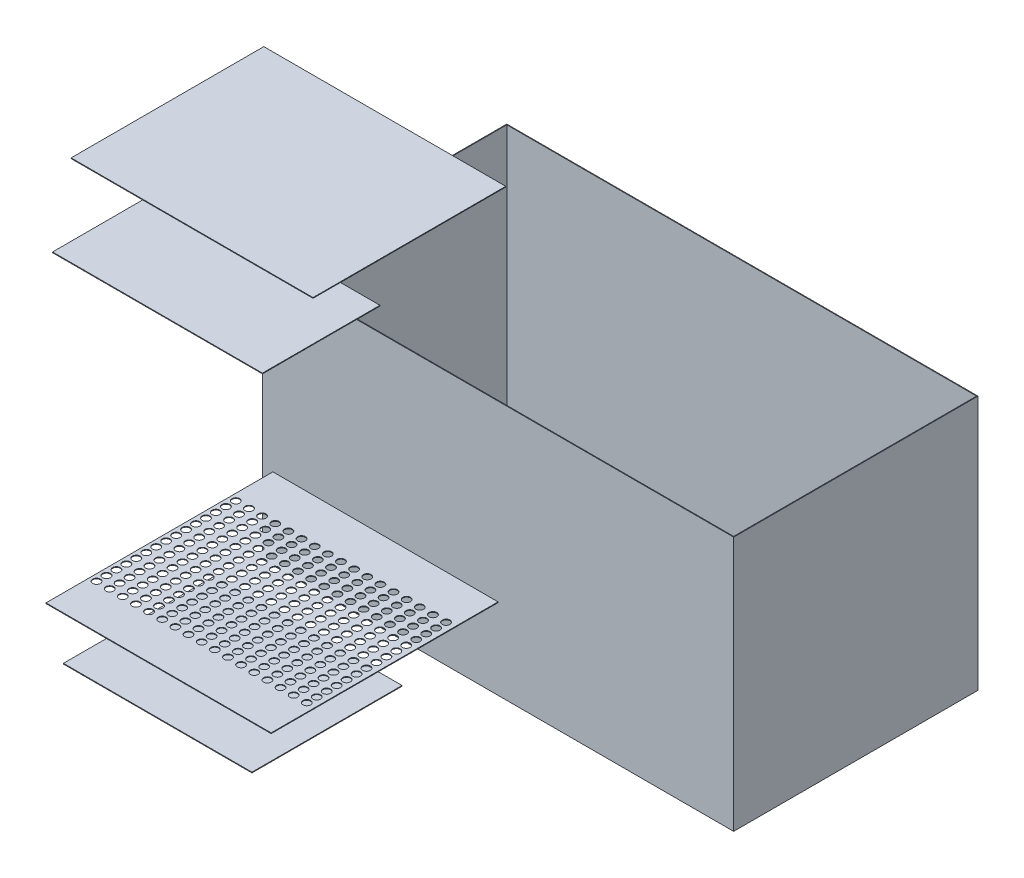
SolidWorks part; units mm, degrees
ref_plane "Спереди" through (0, 0, 0) normal (0, 0, 1) x (1, 0, 0)
ref_plane "Сверху" through (0, 0, 0) normal (0, 1, 0) x (1, 0, 0)
ref_plane "Справа" through (0, 0, 0) normal (1, 0, 0) x (0, 0, -1)
sketch "MASTER_FOOTPRINT" plane through (0, 0, 0) normal (0, 1, 0) x (1, 0, 0)
  line L1 (0, 0) -> (1350, 0)
  line L2 (0, 0) -> (0, 700)
  line L3 (0, 700) -> (1350, 700)
  line L4 (1350, 0) -> (1350, 700)
  dimension "D1" = 1350
  dimension "D2" = 700
extrude "BATH_BASE_PLATE" add sketch "MASTER_FOOTPRINT" along normal blind 750
shell "BATH_SHELL_2MM" thickness 2
sketch "Эскиз1" plane through (0, 0, 0) normal (0, 1, 0) x (1, 0, 0)
  line L1 (80, -220) -> (620, -220)
  line L2 (80, -220) -> (80, -650)
  line L3 (80, -650) -> (620, -650)
  line L4 (620, -220) -> (620, -650)
extrude "INLET_IMPACT_BAFFLE" add sketch "Эскиз1" along normal blind 2 from offset 125 separate body
sketch "Эскиз2" plane through (0, 0, 0) normal (0, 1, 0) x (1, 0, 0)
  line L0 (2, 2) -> (1348, 2) construction
  line L1 (30, 2) -> (675, 2)
  line L2 (30, 2) -> (30, -650)
  line L3 (30, -650) -> (675, -650)
  line L4 (675, 2) -> (675, -650)
  circle A0 centre (48.8235, -125) radius 11
  circle A1 centre (48.8235, -153.5) radius 11
  circle A2 centre (48.8235, -182) radius 11
  circle A3 centre (48.8235, -210.5) radius 11
  circle A4 centre (48.8235, -239) radius 11
  circle A5 centre (48.8235, -267.5) radius 11
  circle A6 centre (48.8235, -296) radius 11
  circle A7 centre (48.8235, -324.5) radius 11
  circle A8 centre (48.8235, -353) radius 11
  circle A9 centre (48.8235, -381.5) radius 11
  circle A10 centre (48.8235, -410) radius 11
  circle A11 centre (48.8235, -438.5) radius 11
  circle A12 centre (48.8235, -467) radius 11
  circle A13 centre (48.8235, -495.5) radius 11
  circle A14 centre (48.8235, -524) radius 11
  circle A15 centre (86.4706, -125) radius 11
  circle A16 centre (86.4706, -153.5) radius 11
  circle A17 centre (86.4706, -182) radius 11
  circle A18 centre (86.4706, -210.5) radius 11
  circle A19 centre (86.4706, -239) radius 11
  circle A20 centre (86.4706, -267.5) radius 11
  circle A21 centre (86.4706, -296) radius 11
  circle A22 centre (86.4706, -324.5) radius 11
  circle A23 centre (86.4706, -353) radius 11
  circle A24 centre (86.4706, -381.5) radius 11
  circle A25 centre (86.4706, -410) radius 11
  circle A26 centre (86.4706, -438.5) radius 11
  circle A27 centre (86.4706, -467) radius 11
  circle A28 centre (86.4706, -495.5) radius 11
  circle A29 centre (86.4706, -524) radius 11
  circle A30 centre (124.1176, -125) radius 11
  circle A31 centre (124.1176, -153.5) radius 11
  circle A32 centre (124.1176, -182) radius 11
  circle A33 centre (124.1176, -210.5) radius 11
  circle A34 centre (124.1176, -239) radius 11
  circle A35 centre (124.1176, -267.5) radius 11
  circle A36 centre (124.1176, -296) radius 11
  circle A37 centre (124.1176, -324.5) radius 11
  circle A38 centre (124.1176, -353) radius 11
  circle A39 centre (124.1176, -381.5) radius 11
  circle A40 centre (124.1176, -410) radius 11
  circle A41 centre (124.1176, -438.5) radius 11
  circle A42 centre (124.1176, -467) radius 11
  circle A43 centre (124.1176, -495.5) radius 11
  circle A44 centre (124.1176, -524) radius 11
  circle A45 centre (161.7647, -125) radius 11
  circle A46 centre (161.7647, -153.5) radius 11
  circle A47 centre (161.7647, -182) radius 11
  circle A48 centre (161.7647, -210.5) radius 11
  circle A49 centre (161.7647, -239) radius 11
  circle A50 centre (161.7647, -267.5) radius 11
  circle A51 centre (161.7647, -296) radius 11
  circle A52 centre (161.7647, -324.5) radius 11
  circle A53 centre (161.7647, -353) radius 11
  circle A54 centre (161.7647, -381.5) radius 11
  circle A55 centre (161.7647, -410) radius 11
  circle A56 centre (161.7647, -438.5) radius 11
  circle A57 centre (161.7647, -467) radius 11
  circle A58 centre (161.7647, -495.5) radius 11
  circle A59 centre (161.7647, -524) radius 11
  circle A60 centre (199.4118, -125) radius 11
  circle A61 centre (199.4118, -153.5) radius 11
  circle A62 centre (199.4118, -182) radius 11
  circle A63 centre (199.4118, -210.5) radius 11
  circle A64 centre (199.4118, -239) radius 11
  circle A65 centre (199.4118, -267.5) radius 11
  circle A66 centre (199.4118, -296) radius 11
  circle A67 centre (199.4118, -324.5) radius 11
  circle A68 centre (199.4118, -353) radius 11
  circle A69 centre (199.4118, -381.5) radius 11
  circle A70 centre (199.4118, -410) radius 11
  circle A71 centre (199.4118, -438.5) radius 11
  circle A72 centre (199.4118, -467) radius 11
  circle A73 centre (199.4118, -495.5) radius 11
  circle A74 centre (199.4118, -524) radius 11
  circle A75 centre (237.0588, -125) radius 11
  circle A76 centre (237.0588, -153.5) radius 11
  circle A77 centre (237.0588, -182) radius 11
  circle A78 centre (237.0588, -210.5) radius 11
  circle A79 centre (237.0588, -239) radius 11
  circle A80 centre (237.0588, -267.5) radius 11
  circle A81 centre (237.0588, -296) radius 11
  circle A82 centre (237.0588, -324.5) radius 11
  circle A83 centre (237.0588, -353) radius 11
  circle A84 centre (237.0588, -381.5) radius 11
  circle A85 centre (237.0588, -410) radius 11
  circle A86 centre (237.0588, -438.5) radius 11
  circle A87 centre (237.0588, -467) radius 11
  circle A88 centre (237.0588, -495.5) radius 11
  circle A89 centre (237.0588, -524) radius 11
  circle A90 centre (274.7059, -125) radius 11
  circle A91 centre (274.7059, -153.5) radius 11
  circle A92 centre (274.7059, -182) radius 11
  circle A93 centre (274.7059, -210.5) radius 11
  circle A94 centre (274.7059, -239) radius 11
  circle A95 centre (274.7059, -267.5) radius 11
  circle A96 centre (274.7059, -296) radius 11
  circle A97 centre (274.7059, -324.5) radius 11
  circle A98 centre (274.7059, -353) radius 11
  circle A99 centre (274.7059, -381.5) radius 11
  circle A100 centre (274.7059, -410) radius 11
  circle A101 centre (274.7059, -438.5) radius 11
  circle A102 centre (274.7059, -467) radius 11
  circle A103 centre (274.7059, -495.5) radius 11
  circle A104 centre (274.7059, -524) radius 11
  circle A105 centre (312.3529, -125) radius 11
  circle A106 centre (312.3529, -153.5) radius 11
  circle A107 centre (312.3529, -182) radius 11
  circle A108 centre (312.3529, -210.5) radius 11
  circle A109 centre (312.3529, -239) radius 11
  circle A110 centre (312.3529, -267.5) radius 11
  circle A111 centre (312.3529, -296) radius 11
  circle A112 centre (312.3529, -324.5) radius 11
  circle A113 centre (312.3529, -353) radius 11
  circle A114 centre (312.3529, -381.5) radius 11
  circle A115 centre (312.3529, -410) radius 11
  circle A116 centre (312.3529, -438.5) radius 11
  circle A117 centre (312.3529, -467) radius 11
  circle A118 centre (312.3529, -495.5) radius 11
  circle A119 centre (312.3529, -524) radius 11
  circle A120 centre (350, -125) radius 11
  circle A121 centre (350, -153.5) radius 11
  circle A122 centre (350, -182) radius 11
  circle A123 centre (350, -210.5) radius 11
  circle A124 centre (350, -239) radius 11
  circle A125 centre (350, -267.5) radius 11
  circle A126 centre (350, -296) radius 11
  circle A127 centre (350, -324.5) radius 11
  circle A128 centre (350, -353) radius 11
  circle A129 centre (350, -381.5) radius 11
  circle A130 centre (350, -410) radius 11
  circle A131 centre (350, -438.5) radius 11
  circle A132 centre (350, -467) radius 11
  circle A133 centre (350, -495.5) radius 11
  circle A134 centre (350, -524) radius 11
  circle A135 centre (387.6471, -125) radius 11
  circle A136 centre (387.6471, -153.5) radius 11
  circle A137 centre (387.6471, -182) radius 11
  circle A138 centre (387.6471, -210.5) radius 11
  circle A139 centre (387.6471, -239) radius 11
  circle A140 centre (387.6471, -267.5) radius 11
  circle A141 centre (387.6471, -296) radius 11
  circle A142 centre (387.6471, -324.5) radius 11
  circle A143 centre (387.6471, -353) radius 11
  circle A144 centre (387.6471, -381.5) radius 11
  circle A145 centre (387.6471, -410) radius 11
  circle A146 centre (387.6471, -438.5) radius 11
  circle A147 centre (387.6471, -467) radius 11
  circle A148 centre (387.6471, -495.5) radius 11
  circle A149 centre (387.6471, -524) radius 11
  circle A150 centre (425.2941, -125) radius 11
  circle A151 centre (425.2941, -153.5) radius 11
  circle A152 centre (425.2941, -182) radius 11
  circle A153 centre (425.2941, -210.5) radius 11
  circle A154 centre (425.2941, -239) radius 11
  circle A155 centre (425.2941, -267.5) radius 11
  circle A156 centre (425.2941, -296) radius 11
  circle A157 centre (425.2941, -324.5) radius 11
  circle A158 centre (425.2941, -353) radius 11
  circle A159 centre (425.2941, -381.5) radius 11
  circle A160 centre (425.2941, -410) radius 11
  circle A161 centre (425.2941, -438.5) radius 11
  circle A162 centre (425.2941, -467) radius 11
  circle A163 centre (425.2941, -495.5) radius 11
  circle A164 centre (425.2941, -524) radius 11
  circle A165 centre (462.9412, -125) radius 11
  circle A166 centre (462.9412, -153.5) radius 11
  circle A167 centre (462.9412, -182) radius 11
  circle A168 centre (462.9412, -210.5) radius 11
  circle A169 centre (462.9412, -239) radius 11
  circle A170 centre (462.9412, -267.5) radius 11
  circle A171 centre (462.9412, -296) radius 11
  circle A172 centre (462.9412, -324.5) radius 11
  circle A173 centre (462.9412, -353) radius 11
  circle A174 centre (462.9412, -381.5) radius 11
  circle A175 centre (462.9412, -410) radius 11
  circle A176 centre (462.9412, -438.5) radius 11
  circle A177 centre (462.9412, -467) radius 11
  circle A178 centre (462.9412, -495.5) radius 11
  circle A179 centre (462.9412, -524) radius 11
  circle A180 centre (500.5882, -125) radius 11
  circle A181 centre (500.5882, -153.5) radius 11
  circle A182 centre (500.5882, -182) radius 11
  circle A183 centre (500.5882, -210.5) radius 11
  circle A184 centre (500.5882, -239) radius 11
  circle A185 centre (500.5882, -267.5) radius 11
  circle A186 centre (500.5882, -296) radius 11
  circle A187 centre (500.5882, -324.5) radius 11
  circle A188 centre (500.5882, -353) radius 11
  circle A189 centre (500.5882, -381.5) radius 11
  circle A190 centre (500.5882, -410) radius 11
  circle A191 centre (500.5882, -438.5) radius 11
  circle A192 centre (500.5882, -467) radius 11
  circle A193 centre (500.5882, -495.5) radius 11
  circle A194 centre (500.5882, -524) radius 11
  circle A195 centre (538.2353, -125) radius 11
  circle A196 centre (538.2353, -153.5) radius 11
  circle A197 centre (538.2353, -182) radius 11
  circle A198 centre (538.2353, -210.5) radius 11
  circle A199 centre (538.2353, -239) radius 11
  circle A200 centre (538.2353, -267.5) radius 11
  circle A201 centre (538.2353, -296) radius 11
  circle A202 centre (538.2353, -324.5) radius 11
  circle A203 centre (538.2353, -353) radius 11
  circle A204 centre (538.2353, -381.5) radius 11
  circle A205 centre (538.2353, -410) radius 11
  circle A206 centre (538.2353, -438.5) radius 11
  circle A207 centre (538.2353, -467) radius 11
  circle A208 centre (538.2353, -495.5) radius 11
  circle A209 centre (538.2353, -524) radius 11
  circle A210 centre (575.8824, -125) radius 11
  circle A211 centre (575.8824, -153.5) radius 11
  circle A212 centre (575.8824, -182) radius 11
  circle A213 centre (575.8824, -210.5) radius 11
  circle A214 centre (575.8824, -239) radius 11
  circle A215 centre (575.8824, -267.5) radius 11
  circle A216 centre (575.8824, -296) radius 11
  circle A217 centre (575.8824, -324.5) radius 11
  circle A218 centre (575.8824, -353) radius 11
  circle A219 centre (575.8824, -381.5) radius 11
  circle A220 centre (575.8824, -410) radius 11
  circle A221 centre (575.8824, -438.5) radius 11
  circle A222 centre (575.8824, -467) radius 11
  circle A223 centre (575.8824, -495.5) radius 11
  circle A224 centre (575.8824, -524) radius 11
  circle A225 centre (613.5294, -125) radius 11
  circle A226 centre (613.5294, -153.5) radius 11
  circle A227 centre (613.5294, -182) radius 11
  circle A228 centre (613.5294, -210.5) radius 11
  circle A229 centre (613.5294, -239) radius 11
  circle A230 centre (613.5294, -267.5) radius 11
  circle A231 centre (613.5294, -296) radius 11
  circle A232 centre (613.5294, -324.5) radius 11
  circle A233 centre (613.5294, -353) radius 11
  circle A234 centre (613.5294, -381.5) radius 11
  circle A235 centre (613.5294, -410) radius 11
  circle A236 centre (613.5294, -438.5) radius 11
  circle A237 centre (613.5294, -467) radius 11
  circle A238 centre (613.5294, -495.5) radius 11
  circle A239 centre (613.5294, -524) radius 11
  circle A240 centre (651.1765, -125) radius 11
  circle A241 centre (651.1765, -153.5) radius 11
  circle A242 centre (651.1765, -182) radius 11
  circle A243 centre (651.1765, -210.5) radius 11
  circle A244 centre (651.1765, -239) radius 11
  circle A245 centre (651.1765, -267.5) radius 11
  circle A246 centre (651.1765, -296) radius 11
  circle A247 centre (651.1765, -324.5) radius 11
  circle A248 centre (651.1765, -353) radius 11
  circle A249 centre (651.1765, -381.5) radius 11
  circle A250 centre (651.1765, -410) radius 11
  circle A251 centre (651.1765, -438.5) radius 11
  circle A252 centre (651.1765, -467) radius 11
  circle A253 centre (651.1765, -495.5) radius 11
  circle A254 centre (651.1765, -524) radius 11
extrude "DISTRIBUTOR_D22" add sketch "Эскиз2" along normal blind 2 from offset 250 separate body
sketch "Эскиз3" plane through (0, 0, 0) normal (0, 1, 0) x (1, 0, 0)
  line L0 (30, -650) -> (675, -650) construction
  line L1 (48.8235, -313.5) -> (650, -313.5)
  line L2 (48.8235, -313.5) -> (48.8235, -650)
  line L3 (48.8235, -650) -> (650, -650)
  line L4 (650, -313.5) -> (650, -650)
  circle A0 centre (48.8235, -324.5) radius 11 construction
extrude "OUTLET_SUBMERGED_BAFFLE" add sketch "Эскиз3" along normal blind 2 from offset 1130 separate body
sketch "Эскиз4" plane through (0, 0, 0) normal (0, 1, 0) x (1, 0, 0)
  line L1 (2, 2) -> (695, 2)
  line L2 (2, 2) -> (2, -550)
  line L3 (2, -550) -> (695, -550)
  line L4 (695, 2) -> (695, -550)
extrude "OVERFLOW_WEIR_Z550" add sketch "Эскиз4" along normal blind 2 from offset 1290 separate body
sketch "Эскиз5" plane through (0, 0, 0) normal (0, 1, 0) x (1, 0, 0)
  circle A0 centre (350, -420) radius 50
sketch "Эскиз6" plane through (0, 0, 0) normal (0, 1, 0) x (1, 0, 0)
  line L0 (2, -550) -> (695, -550) construction
  line L1 (50, -550) -> (650, -550)
  line L2 (50, -550) -> (50, -720)
  line L3 (50, -720) -> (650, -720)
  line L4 (650, -550) -> (650, -720)
extrude "INLET_D100_OPENING" cut sketch "Эскиз5" along normal blind 20 flip side to cut
equation "\"AI_Q_Peak\"= 0.006"
equation "\"AI_B_Bath\"= 700"
equation "\"AI_L_Settle\"= 900"
equation "\"AI_L_Inlet\"= 250"
equation "\"AI_L_Outlet\"= 200"
equation "\"AI_L_Bath\"= 1350"
equation "\"AI_H_Water\"= 550"
equation "\"AI_H_Freeboard\"= 200"
equation "\"AI_H_Bath\"= 750"
equation "\"AI_Shell_Thickness\"= 2"
equation "\"AI_Inlet_DN\"= 100"
equation "\"AI_Weir_Width\"= 600"
equation "\"AI_Inlet_Baffle_Offset\"= 125"
equation "\"AI_Distributor_Open_Area\"= 0.28"
equation "\"AI_Distributor_Hole_Dia\"= 22"
equation "\"AI_Distributor_Blind_Zone\"= 110"
equation "\"AI_Outlet_Baffle_Depth\"= 250"
equation "\"AI_Screw_Diameter\"= 100"
equation "\"AI_Screw_Pitch\"= 100"
equation "\"AI_Screw_Angle\"= 30"
equation "\"AI_Screw_Rpm\"= 15"
equation "\"AI_Screw_Clearance\"= 5"
equation "\"AI_Liner_Thickness\"= 5"
equation "\"AI_Discharge_Height\"= 650"
equation "\"AI_Frame_Height\"= 500"
equation "\"D1@MASTER_FOOTPRINT\" = \"AI_L_Bath\""
equation "\"D2@MASTER_FOOTPRINT\" = \"AI_B_Bath\""
equation "\"D1@BATH_BASE_PLATE\" = \"AI_H_Bath\""
